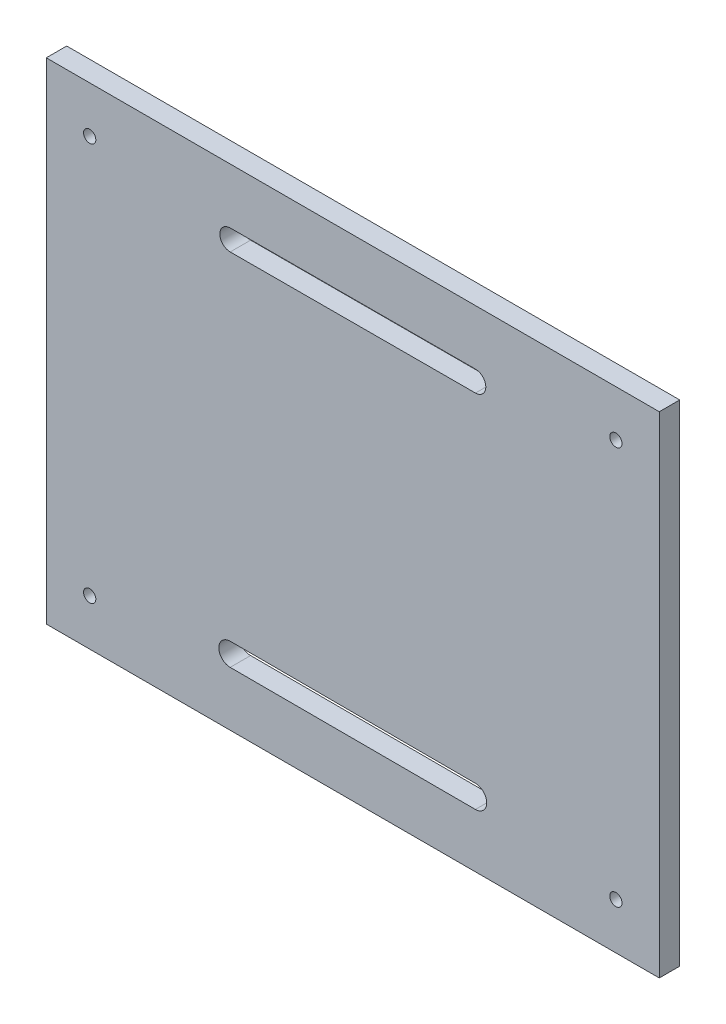
SolidWorks part; units mm, degrees
material "Acrylic (Medium-high impact)"
ref_plane "Front Plane" through (0, 0, 0) normal (0, 0, 1) x (1, 0, 0)
ref_plane "Top Plane" through (0, 0, 0) normal (0, 1, 0) x (1, 0, 0)
ref_plane "Right Plane" through (0, 0, 0) normal (1, 0, 0) x (0, 0, -1)
sketch "Model" plane through (0, 0, 0) normal (0, 0, 1) x (1, 0, 0)
  line L0 (11.5556, 9.1431) -> (161.5556, 9.1431)
  line L1 (161.5556, 9.1431) -> (161.5556, 129.1431)
  line L2 (161.5556, 129.1431) -> (11.5556, 129.1431)
  line L3 (11.5556, 129.1431) -> (11.5556, 9.1431)
  line L4 (56.556, 115.4395) -> (116.5556, 115.6506)
  line L5 (116.5556, 110.6506) -> (56.5556, 110.6506)
  line L6 (56.556, 22.8466) -> (116.5556, 22.6355)
  line L7 (116.5556, 27.6355) -> (56.5556, 27.6355)
  circle A0 centre (22.179, 117.8229) radius 1.5
  circle A1 centre (150.9322, 117.8229) radius 1.5
  circle A2 centre (22.179, 20.4633) radius 1.5
  circle A3 centre (150.9322, 20.4633) radius 1.5
  arc A4 (116.5556, 110.6506) -> (116.5556, 115.6506) centre (116.5644, 113.1506) ccw
  arc A5 (56.5388, 115.4395) -> (56.5556, 110.6506) centre (56.5556, 113.0451) ccw
  arc A6 (116.5556, 22.6355) -> (116.5556, 27.6355) centre (116.5644, 25.1355) ccw
  arc A7 (56.5556, 27.6355) -> (56.5388, 22.8467) centre (56.5556, 25.2411) ccw
extrude "Boss-Extrude1" add sketch "Model" along normal blind 5
sketch "Sketch2" plane through (0, 0, 5) normal (0, 0, 1) x (1, 0, 0)
  line L0 (56.5556, 113.0451) -> (116.5644, 113.1506) construction
  line L1 (56.5511, 115.5856) -> (116.5599, 115.6911)
  line L2 (56.5601, 110.5046) -> (116.5689, 110.6101)
  line L3 (56.5556, 25.2411) -> (116.5644, 25.1355) construction
  line L4 (56.5605, 28.0109) -> (116.5693, 27.9053)
  line L5 (56.5507, 22.4713) -> (116.5595, 22.3657)
  arc A0 (56.5511, 115.5856) -> (56.5601, 110.5046) centre (56.5556, 113.0451) ccw
  arc A1 (116.5689, 110.6101) -> (116.5599, 115.6911) centre (116.5644, 113.1506) ccw
  arc A2 (56.5605, 28.0109) -> (56.5507, 22.4713) centre (56.5556, 25.2411) ccw
  arc A3 (116.5595, 22.3657) -> (116.5693, 27.9053) centre (116.5644, 25.1355) ccw
  point P4 (86.56, 113.0979)
  point P9 (86.56, 25.1883)
extrude "Cut-Extrude1" cut sketch "Sketch2" against normal through all
